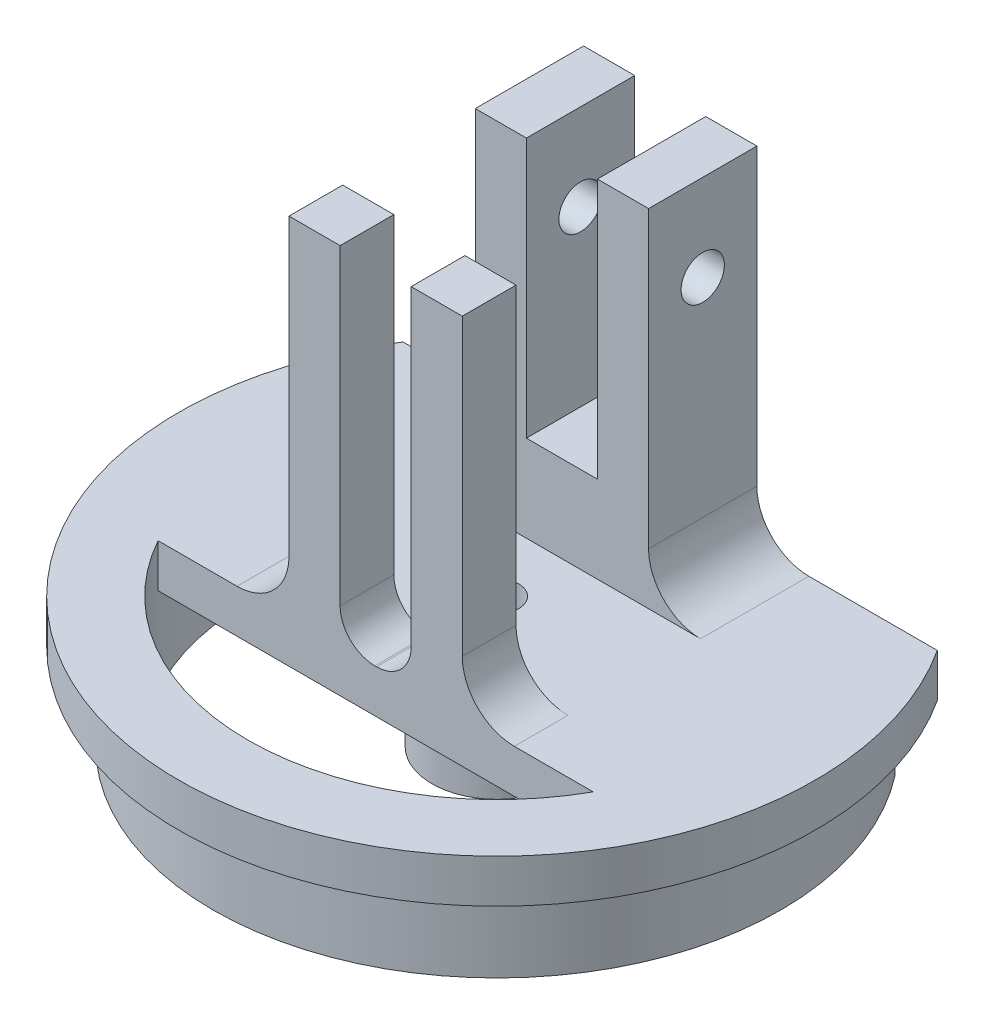
SolidWorks part; units mm, degrees
ref_plane "Спереди" through (0, 0, 0) normal (0, 0, 1) x (1, 0, 0)
ref_plane "Сверху" through (0, 0, 0) normal (0, 1, 0) x (1, 0, 0)
ref_plane "Справа" through (0, 0, 0) normal (1, 0, 0) x (0, 0, -1)
sketch "Эскиз1" plane through (0, 0, 0) normal (0, 1, 0) x (1, 0, 0)
  circle A0 centre (0, 0) radius 2.5
  circle A1 centre (0, 0) radius 7.5
  dimension "D1" = 15
  dimension "D2" = 5
extrude "cylinder" add sketch "Эскиз1" along normal blind 5 and the other way blind 10
sketch "Эскиз2" plane through (0, 0, 0) normal (0, 1, 0) x (1, 0, 0)
  circle A0 centre (0, 0) radius 36.75
  circle A1 centre (0, 0) radius 2.5
  dimension "D1" = 73.5
  dimension "D2" = 5
extrude "base horizont" add sketch "Эскиз2" along normal blind 5
sketch "Эскиз3" plane through (0, 5, 0) normal (0, 1, 0) x (1, 0, 0)
  circle A0 centre (0, 0) radius 28.75
  circle A1 centre (0, 0) radius 32.75
  dimension "D1" = 57.5
  dimension "D2" = 65.5
extrude "edge" add sketch "Эскиз3" against normal blind 15
sketch "Эскиз4" plane through (0, 5, 0) normal (0, 1, 0) x (1, 0, 0)
  line L1 (-10, 2.5) -> (10, 2.5)
  line L2 (-10, 2.5) -> (-10, 20)
  line L3 (-10, 20) -> (10, 20)
  line L4 (10, 2.5) -> (10, 20)
  circle A1 centre (0, 0) radius 2.5 construction
  point P4 (0, 2.5)
  dimension "D1" = 20
  dimension "D2" = 20
extrude "rectangle" add sketch "Эскиз4" along normal blind 40 and the other way up to surface other way up to face at (0, -10, 28.75)
sketch "Эскиз6" plane through (0, 45, 0) normal (0, 1, 0) x (1, 0, 0)
  line L0 (10, 20) -> (-10, 20) construction
  line L1 (-4.1, 20) -> (4.1, 20)
  line L2 (-4.1, 20) -> (-4.1, 2.5)
  line L3 (-4.1, 2.5) -> (4.1, 2.5)
  line L4 (4.1, 20) -> (4.1, 2.5)
  line L6 (0, 0) -> (0, -39.8296) construction
  line L7 (-10, 2.5) -> (10, 2.5) construction
  point P9 (0, 20)
  dimension "D1" = 8.2
extrude "Вытянуть5" cut sketch "Эскиз6" against normal blind 30
sketch "Эскиз7" plane through (10, 0, 0) normal (1, 0, 0) x (0, 0, -1)
  line L4 (20, 45) -> (20, 5) construction
  line L5 (2.5, 45) -> (20, 45) construction
  circle A0 centre (13.75, 35) radius 2.5
  dimension "D3" = 5
  dimension "D1" = 6.25
  dimension "D2" = 10
extrude "Вытянуть6" cut sketch "Эскиз7" against normal up to surface (20 mm away) up to face at (-10, 25, -11.25)
sketch "Эскиз8" plane through (0, 0, 0) normal (0, 1, 0) x (1, 0, 0)
  line L1 (-30.8312, 36.75) -> (30.8312, 36.75)
  line L2 (-30.8312, 36.75) -> (-30.8312, 20)
  line L3 (-30.8312, 20) -> (30.8312, 20)
  line L4 (30.8312, 36.75) -> (30.8312, 20)
  circle A1 centre (0, 0) radius 36.75 construction
  dimension "D1" = 20
extrude "Вытянуть7" cut sketch "Эскиз8" along normal up to next and the other way up to next
sketch "Эскиз9" plane through (0, 45, 0) normal (0, 1, 0) x (1, 0, 0)
  line L0 (10, 2.5) -> (10, 20) construction
  line L1 (-10, 2.5) -> (10, 2.5)
  line L2 (-10, 2.5) -> (-10, 7.5)
  line L3 (-10, 7.5) -> (10, 7.5)
  line L4 (10, 2.5) -> (10, 7.5)
  dimension "D2" = 5
extrude "Вытянуть8" cut sketch "Эскиз9" against normal up to surface (40 mm away)
sketch "Эскиз10" plane through (0, 5, 0) normal (0, 1, 0) x (1, 0, 0)
  line L0 (0, -14) -> (45.2157, -14) construction
  line L1 (-25.111, -14) -> (25.111, -14)
  arc A0 (-25.111, -14) -> (25.111, -14) centre (0, 0) ccw
  arc A6 (-20.6534, 20) -> (20.6534, 20) centre (0, 0) ccw construction
  dimension "D1" = 14
extrude "pie" cut sketch "Эскиз10" against normal up to next
sketch "Эскиз11" plane through (0, 5, 0) normal (0, 1, 0) x (1, 0, 0)
  line L0 (-10, -7.8) -> (-10, -14)
  line L1 (25.111, -14) -> (-25.111, -14) construction
  line L2 (-10, -14) -> (-4.1, -14)
  line L3 (-4.1, -14) -> (-4.1, -7.8)
  line L4 (-4.1, -7.8) -> (-10, -7.8)
  line L5 (-4.1, 7.5) -> (-10, 7.5) construction
  line L6 (0, 0) -> (0, -14) construction
  line L7 (4.1, -7.8) -> (10, -7.8)
  line L8 (4.1, -14) -> (4.1, -7.8)
  line L9 (10, -14) -> (4.1, -14)
  line L10 (10, -7.8) -> (10, -14)
  line L11 (-10, 7.5) -> (10, 7.5) construction
  dimension "D1" = 15.3
extrude "Вытянуть9" add sketch "Эскиз11" along normal up to surface (40 mm away) up to face at (-7.05, 45, -13.75)
fillet "Скругление4" radius 6 4 edges at (-10, 5, 10.9) (-10, 5, -13.75) (10, 5, -13.75) (10, 5, 10.9)
fillet "Скругление5" radius 4 2 edges at (-4.1, 5, 10.9) (4.1, 5, 10.9)
